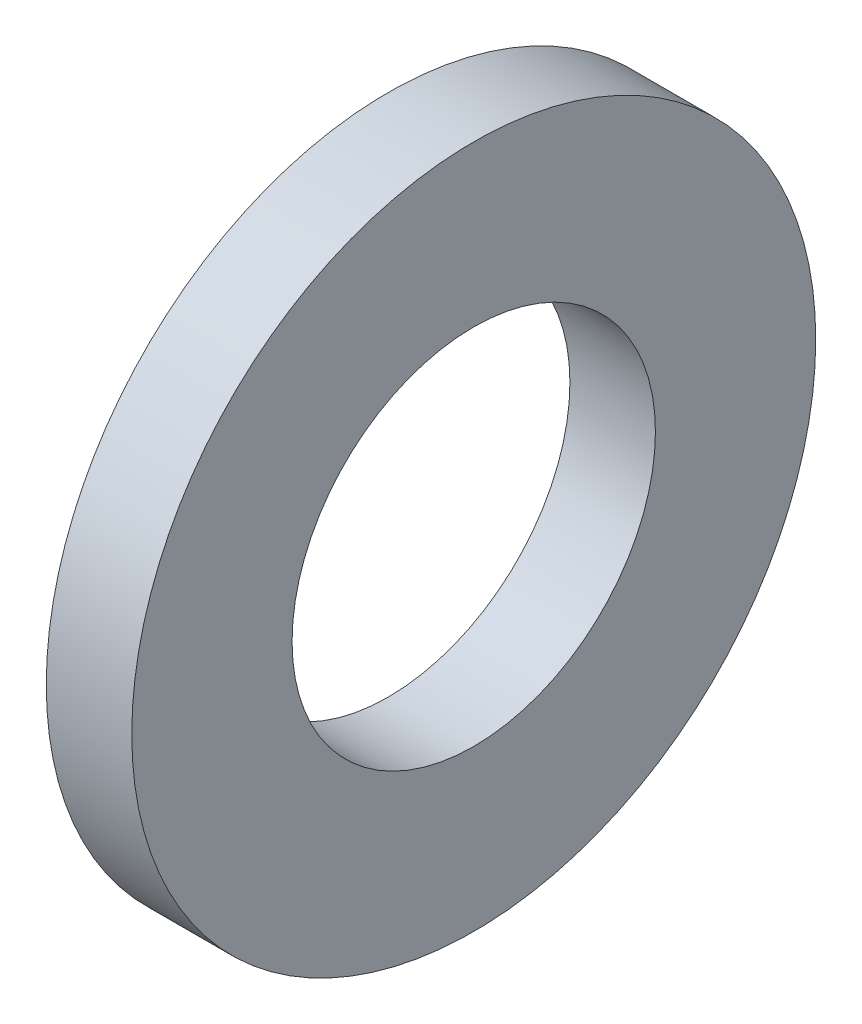
SolidWorks part; units mm, degrees
ref_plane "前视基准面" through (0, 0, 0) normal (0, 0, 1) x (1, 0, 0)
ref_plane "上视基准面" through (0, 0, 0) normal (0, 1, 0) x (1, 0, 0)
ref_plane "右视基准面" through (0, 0, 0) normal (1, 0, 0) x (0, 0, -1)
sketch "草图1" plane through (0, 0, 0) normal (1, 0, 0) x (0, 0, -1)
  circle A0 centre (0, 0) radius 3.2
  circle A1 centre (0, 0) radius 1.7
extrude "凸台-拉伸1" add sketch "草图1" along normal blind 0.8
